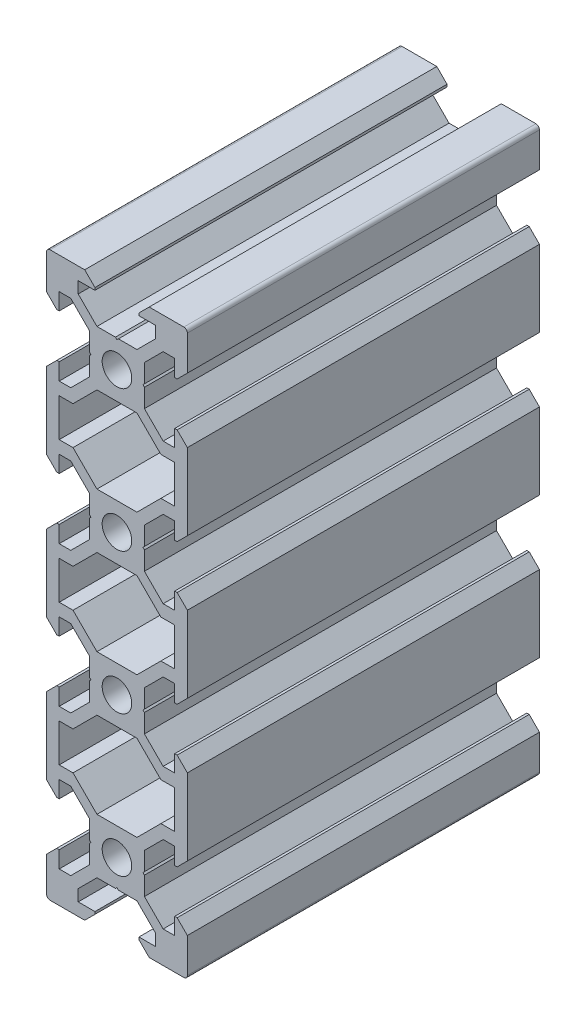
SolidWorks part; units mm, degrees
material "6061-T6 (SS)"
ref_plane "Front Plane" through (0, 0, 0) normal (0, 0, 1) x (1, 0, 0)
ref_plane "Top Plane" through (0, 0, 0) normal (0, 1, 0) x (1, 0, 0)
ref_plane "Right Plane" through (0, 0, 0) normal (1, 0, 0) x (0, 0, -1)
sketch "Sketch1" plane through (0, 0, 0) normal (0, 0, 1) x (1, 0, 0)
  line L0 (0, 0) -> (10, 0) construction
  line L1 (9.5, -40) -> (-9.5, -40)
  line L2 (10, -39.5) -> (10, 39.5)
  line L3 (9.5, 40) -> (-9.5, 40)
  line L4 (-10, -39.5) -> (-10, 39.5)
  line L5 (10, -40) -> (-10, 40) construction
  line L6 (10, 40) -> (-10, -40) construction
  circle A0 centre (0, 30) radius 2.1
  circle A1 centre (0, 10) radius 2.1
  circle A2 centre (0, -10) radius 2.1
  circle A3 centre (0, -30) radius 2.1
  arc A4 (-9.5, -40) -> (-10, -39.5) centre (-9.5, -39.5) cw
  arc A5 (9.5, -40) -> (10, -39.5) centre (9.5, -39.5) ccw
  arc A6 (10, 39.5) -> (9.5, 40) centre (9.5, 39.5) ccw
  arc A7 (-9.5, 40) -> (-10, 39.5) centre (-9.5, 39.5) ccw
  point P0 (0, 0)
  line B0 (0, 30) -> (0, 40) construction
  line B1 (0, 33.69) -> (-0.21, 33.9)
  line B2 (-0.21, 33.9) -> (-2.8393, 33.9)
  line B3 (-2.8393, 33.9) -> (-5.5, 36.5607)
  line B4 (-5.5, 36.5607) -> (-5.5, 38.2)
  line B5 (-5.5, 38.2) -> (-3.125, 38.2)
  line B6 (-3.125, 38.2) -> (-3.125, 38.545)
  line B7 (-3.125, 38.545) -> (-4.58, 40)
  line B8 (-4.58, 40) -> (4.58, 40)
  line B9 (0, 30) -> (-5.9132, 35.9132) construction
  line B10 (3.125, 38.545) -> (4.58, 40)
  line B11 (3.125, 38.2) -> (3.125, 38.545)
  line B12 (5.5, 38.2) -> (3.125, 38.2)
  line B13 (5.5, 36.5607) -> (5.5, 38.2)
  line B14 (2.8393, 33.9) -> (5.5, 36.5607)
  line B15 (0.21, 33.9) -> (2.8393, 33.9)
  line B16 (0, 33.69) -> (0.21, 33.9)
  line B17 (0, 30) -> (-10, 30) construction
  line B18 (-3.69, 30) -> (-3.9, 29.79)
  line B19 (-3.9, 29.79) -> (-3.9, 27.1607)
  line B20 (-3.9, 27.1607) -> (-6.5607, 24.5)
  line B21 (-6.5607, 24.5) -> (-8.2, 24.5)
  line B22 (-8.2, 24.5) -> (-8.2, 26.875)
  line B23 (-8.2, 26.875) -> (-8.545, 26.875)
  line B24 (-8.545, 26.875) -> (-10, 25.42)
  line B25 (-10, 25.42) -> (-10, 34.58)
  line B26 (0, 30) -> (-5.9132, 24.0868) construction
  line B27 (-8.545, 33.125) -> (-10, 34.58)
  line B28 (-8.2, 33.125) -> (-8.545, 33.125)
  line B29 (-8.2, 35.5) -> (-8.2, 33.125)
  line B30 (-6.5607, 35.5) -> (-8.2, 35.5)
  line B31 (-3.9, 32.8393) -> (-6.5607, 35.5)
  line B32 (-3.9, 30.21) -> (-3.9, 32.8393)
  line B33 (-3.69, 30) -> (-3.9, 30.21)
  line B34 (0, 10) -> (-10, 10) construction
  line B35 (-3.69, 10) -> (-3.9, 9.79)
  line B36 (-3.9, 9.79) -> (-3.9, 7.1607)
  line B37 (-3.9, 7.1607) -> (-6.5607, 4.5)
  line B38 (-6.5607, 4.5) -> (-8.2, 4.5)
  line B39 (-8.2, 4.5) -> (-8.2, 6.875)
  line B40 (-8.2, 6.875) -> (-8.545, 6.875)
  line B41 (-8.545, 6.875) -> (-10, 5.42)
  line B42 (-10, 5.42) -> (-10, 14.58)
  line B43 (0, 10) -> (-5.9132, 4.0868) construction
  line B44 (-8.545, 13.125) -> (-10, 14.58)
  line B45 (-8.2, 13.125) -> (-8.545, 13.125)
  line B46 (-8.2, 15.5) -> (-8.2, 13.125)
  line B47 (-6.5607, 15.5) -> (-8.2, 15.5)
  line B48 (-3.9, 12.8393) -> (-6.5607, 15.5)
  line B49 (-3.9, 10.21) -> (-3.9, 12.8393)
  line B50 (-3.69, 10) -> (-3.9, 10.21)
  line B51 (0, -10) -> (-10, -10) construction
  line B52 (-3.69, -10) -> (-3.9, -10.21)
  line B53 (-3.9, -10.21) -> (-3.9, -12.8393)
  line B54 (-3.9, -12.8393) -> (-6.5607, -15.5)
  line B55 (-6.5607, -15.5) -> (-8.2, -15.5)
  line B56 (-8.2, -15.5) -> (-8.2, -13.125)
  line B57 (-8.2, -13.125) -> (-8.545, -13.125)
  line B58 (-8.545, -13.125) -> (-10, -14.58)
  line B59 (-10, -14.58) -> (-10, -5.42)
  line B60 (0, -10) -> (-5.9132, -15.9132) construction
  line B61 (-8.545, -6.875) -> (-10, -5.42)
  line B62 (-8.2, -6.875) -> (-8.545, -6.875)
  line B63 (-8.2, -4.5) -> (-8.2, -6.875)
  line B64 (-6.5607, -4.5) -> (-8.2, -4.5)
  line B65 (-3.9, -7.1607) -> (-6.5607, -4.5)
  line B66 (-3.9, -9.79) -> (-3.9, -7.1607)
  line B67 (-3.69, -10) -> (-3.9, -9.79)
  line B68 (0, -30) -> (-10, -30) construction
  line B69 (-3.69, -30) -> (-3.9, -30.21)
  line B70 (-3.9, -30.21) -> (-3.9, -32.8393)
  line B71 (-3.9, -32.8393) -> (-6.5607, -35.5)
  line B72 (-6.5607, -35.5) -> (-8.2, -35.5)
  line B73 (-8.2, -35.5) -> (-8.2, -33.125)
  line B74 (-8.2, -33.125) -> (-8.545, -33.125)
  line B75 (-8.545, -33.125) -> (-10, -34.58)
  line B76 (-10, -34.58) -> (-10, -25.42)
  line B77 (0, -30) -> (-5.9132, -35.9132) construction
  line B78 (-8.545, -26.875) -> (-10, -25.42)
  line B79 (-8.2, -26.875) -> (-8.545, -26.875)
  line B80 (-8.2, -24.5) -> (-8.2, -26.875)
  line B81 (-6.5607, -24.5) -> (-8.2, -24.5)
  line B82 (-3.9, -27.1607) -> (-6.5607, -24.5)
  line B83 (-3.9, -29.79) -> (-3.9, -27.1607)
  line B84 (-3.69, -30) -> (-3.9, -29.79)
  line B85 (0, -30) -> (0, -40) construction
  line B86 (0, -33.69) -> (0.21, -33.9)
  line B87 (0.21, -33.9) -> (2.8393, -33.9)
  line B88 (2.8393, -33.9) -> (5.5, -36.5607)
  line B89 (5.5, -36.5607) -> (5.5, -38.2)
  line B90 (5.5, -38.2) -> (3.125, -38.2)
  line B91 (3.125, -38.2) -> (3.125, -38.545)
  line B92 (3.125, -38.545) -> (4.58, -40)
  line B93 (4.58, -40) -> (-4.58, -40)
  line B94 (0, -30) -> (5.9132, -35.9132) construction
  line B95 (-3.125, -38.545) -> (-4.58, -40)
  line B96 (-3.125, -38.2) -> (-3.125, -38.545)
  line B97 (-5.5, -38.2) -> (-3.125, -38.2)
  line B98 (-5.5, -36.5607) -> (-5.5, -38.2)
  line B99 (-2.8393, -33.9) -> (-5.5, -36.5607)
  line B100 (-0.21, -33.9) -> (-2.8393, -33.9)
  line B101 (0, -33.69) -> (-0.21, -33.9)
  line B102 (0, -30) -> (10, -30) construction
  line B103 (3.69, -30) -> (3.9, -29.79)
  line B104 (3.9, -29.79) -> (3.9, -27.1607)
  line B105 (3.9, -27.1607) -> (6.5607, -24.5)
  line B106 (6.5607, -24.5) -> (8.2, -24.5)
  line B107 (8.2, -24.5) -> (8.2, -26.875)
  line B108 (8.2, -26.875) -> (8.545, -26.875)
  line B109 (8.545, -26.875) -> (10, -25.42)
  line B110 (10, -25.42) -> (10, -34.58)
  line B111 (0, -30) -> (5.9132, -24.0868) construction
  line B112 (8.545, -33.125) -> (10, -34.58)
  line B113 (8.2, -33.125) -> (8.545, -33.125)
  line B114 (8.2, -35.5) -> (8.2, -33.125)
  line B115 (6.5607, -35.5) -> (8.2, -35.5)
  line B116 (3.9, -32.8393) -> (6.5607, -35.5)
  line B117 (3.9, -30.21) -> (3.9, -32.8393)
  line B118 (3.69, -30) -> (3.9, -30.21)
  line B119 (0, -10) -> (10, -10) construction
  line B120 (3.69, -10) -> (3.9, -9.79)
  line B121 (3.9, -9.79) -> (3.9, -7.1607)
  line B122 (3.9, -7.1607) -> (6.5607, -4.5)
  line B123 (6.5607, -4.5) -> (8.2, -4.5)
  line B124 (8.2, -4.5) -> (8.2, -6.875)
  line B125 (8.2, -6.875) -> (8.545, -6.875)
  line B126 (8.545, -6.875) -> (10, -5.42)
  line B127 (10, -5.42) -> (10, -14.58)
  line B128 (0, -10) -> (5.9132, -4.0868) construction
  line B129 (8.545, -13.125) -> (10, -14.58)
  line B130 (8.2, -13.125) -> (8.545, -13.125)
  line B131 (8.2, -15.5) -> (8.2, -13.125)
  line B132 (6.5607, -15.5) -> (8.2, -15.5)
  line B133 (3.9, -12.8393) -> (6.5607, -15.5)
  line B134 (3.9, -10.21) -> (3.9, -12.8393)
  line B135 (3.69, -10) -> (3.9, -10.21)
  line B136 (0, 10) -> (10, 10) construction
  line B137 (3.69, 10) -> (3.9, 10.21)
  line B138 (3.9, 10.21) -> (3.9, 12.8393)
  line B139 (3.9, 12.8393) -> (6.5607, 15.5)
  line B140 (6.5607, 15.5) -> (8.2, 15.5)
  line B141 (8.2, 15.5) -> (8.2, 13.125)
  line B142 (8.2, 13.125) -> (8.545, 13.125)
  line B143 (8.545, 13.125) -> (10, 14.58)
  line B144 (10, 14.58) -> (10, 5.42)
  line B145 (0, 10) -> (5.9132, 15.9132) construction
  line B146 (8.545, 6.875) -> (10, 5.42)
  line B147 (8.2, 6.875) -> (8.545, 6.875)
  line B148 (8.2, 4.5) -> (8.2, 6.875)
  line B149 (6.5607, 4.5) -> (8.2, 4.5)
  line B150 (3.9, 7.1607) -> (6.5607, 4.5)
  line B151 (3.9, 9.79) -> (3.9, 7.1607)
  line B152 (3.69, 10) -> (3.9, 9.79)
  line B153 (0, 30) -> (10, 30) construction
  line B154 (3.69, 30) -> (3.9, 30.21)
  line B155 (3.9, 30.21) -> (3.9, 32.8393)
  line B156 (3.9, 32.8393) -> (6.5607, 35.5)
  line B157 (6.5607, 35.5) -> (8.2, 35.5)
  line B158 (8.2, 35.5) -> (8.2, 33.125)
  line B159 (8.2, 33.125) -> (8.545, 33.125)
  line B160 (8.545, 33.125) -> (10, 34.58)
  line B161 (10, 34.58) -> (10, 25.42)
  line B162 (0, 30) -> (5.9132, 35.9132) construction
  line B163 (8.545, 26.875) -> (10, 25.42)
  line B164 (8.2, 26.875) -> (8.545, 26.875)
  line B165 (8.2, 24.5) -> (8.2, 26.875)
  line B166 (6.5607, 24.5) -> (8.2, 24.5)
  line B167 (3.9, 27.1607) -> (6.5607, 24.5)
  line B168 (3.9, 29.79) -> (3.9, 27.1607)
  line B169 (3.69, 30) -> (3.9, 29.79)
  line B170 (-8.2, 17.3) -> (-8.2, 22.7)
  line B171 (-8.2, 22.7) -> (-6.2393, 22.7)
  line B172 (-6.2393, 22.7) -> (-2.8393, 26.1)
  line B173 (-2.8393, 26.1) -> (2.8393, 26.1)
  line B174 (0, 26.1) -> (0, 20) construction
  line B175 (0, 20) -> (-8.2, 20) construction
  line B176 (6.2393, 22.7) -> (2.8393, 26.1)
  line B177 (8.2, 22.7) -> (6.2393, 22.7)
  line B178 (8.2, 17.3) -> (8.2, 22.7)
  line B179 (8.2, 17.3) -> (6.2393, 17.3)
  line B180 (6.2393, 17.3) -> (2.8393, 13.9)
  line B181 (-2.8393, 13.9) -> (2.8393, 13.9)
  line B182 (-6.2393, 17.3) -> (-2.8393, 13.9)
  line B183 (-8.2, 17.3) -> (-6.2393, 17.3)
  line B184 (0, 26.1) -> (0, 30) construction
  line B185 (0, 30) -> (-5.0927, 24.9073) construction
  line B186 (-8.2, -2.7) -> (-8.2, 2.7)
  line B187 (-8.2, 2.7) -> (-6.2393, 2.7)
  line B188 (-6.2393, 2.7) -> (-2.8393, 6.1)
  line B189 (-2.8393, 6.1) -> (2.8393, 6.1)
  line B190 (0, 6.1) -> (0, 0) construction
  line B191 (0, 0) -> (-8.2, 0) construction
  line B192 (6.2393, 2.7) -> (2.8393, 6.1)
  line B193 (8.2, 2.7) -> (6.2393, 2.7)
  line B194 (8.2, -2.7) -> (8.2, 2.7)
  line B195 (8.2, -2.7) -> (6.2393, -2.7)
  line B196 (6.2393, -2.7) -> (2.8393, -6.1)
  line B197 (-2.8393, -6.1) -> (2.8393, -6.1)
  line B198 (-6.2393, -2.7) -> (-2.8393, -6.1)
  line B199 (-8.2, -2.7) -> (-6.2393, -2.7)
  line B200 (0, 6.1) -> (0, 10) construction
  line B201 (0, 10) -> (-5.0927, 4.9073) construction
  line B202 (-8.2, -22.7) -> (-8.2, -17.3)
  line B203 (-8.2, -17.3) -> (-6.2393, -17.3)
  line B204 (-6.2393, -17.3) -> (-2.8393, -13.9)
  line B205 (-2.8393, -13.9) -> (2.8393, -13.9)
  line B206 (0, -13.9) -> (0, -20) construction
  line B207 (0, -20) -> (-8.2, -20) construction
  line B208 (6.2393, -17.3) -> (2.8393, -13.9)
  line B209 (8.2, -17.3) -> (6.2393, -17.3)
  line B210 (8.2, -22.7) -> (8.2, -17.3)
  line B211 (8.2, -22.7) -> (6.2393, -22.7)
  line B212 (6.2393, -22.7) -> (2.8393, -26.1)
  line B213 (-2.8393, -26.1) -> (2.8393, -26.1)
  line B214 (-6.2393, -22.7) -> (-2.8393, -26.1)
  line B215 (-8.2, -22.7) -> (-6.2393, -22.7)
  line B216 (0, -13.9) -> (0, -10) construction
  line B217 (0, -10) -> (-5.0927, -15.0927) construction
  dimension "D5" = 4.2
  dimension "D6" = 0.5
  dimension "D1" = 20
  dimension "D2" = 80
  dimension "D3" = 20
  dimension "D4" = 20
sketch_block_instance "V Slot 1-4"
sketch_block "V Slot 1" parameters "D1"=10, "D2"=11, "D3"=4.3, "D4"=1.8, "D5"=0.21, "D6"=45, "D7"=9.16, "D8"=1.5, "D9"=6.25
sketch_block_instance "V Slot 1-5"
sketch_block_instance "V Slot 1-6"
sketch_block_instance "V Slot 1-7"
sketch_block_instance "V Slot 1-8"
sketch_block_instance "V Slot 1-9"
sketch_block_instance "V Slot 1-10"
sketch_block_instance "V Slot 1-11"
sketch_block_instance "V Slot 1-12"
sketch_block_instance "V Slot 1-13"
sketch_block_instance "Center Cutout 1-1"
sketch_block "Center Cutout 1" parameters "D1"=5.4, "D2"=12.2, "D3"=8.2, "D4"=45, "D5"=10, "D6"=1.5
sketch_block_instance "Center Cutout 1-2"
sketch_block_instance "Center Cutout 1-3"
extrude "Boss-Extrude1" add sketch "Sketch1" along normal blind 50 contours B169 B154 B155 B156 B157 B158 B159 B160 L2 A6 L3 B10 B11 B12 B13 B14 B15 B16 B1 B2 B3 B4 B5 B6 B7 A7 L4 B27 B28 B29 B30 B31 B32 B33 B18 B19 B20 B21 B22 B23 B24 B44 B45 B46 B47 B48 B49 B50 B35
